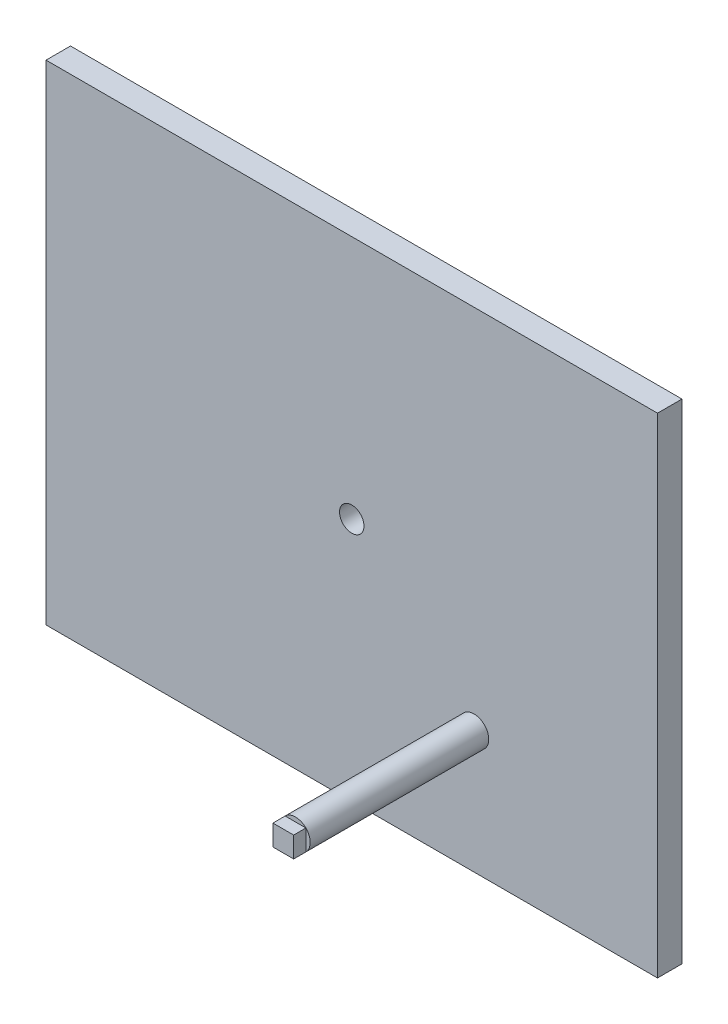
SolidWorks part; units mm, degrees
ref_plane "前视基准面" through (0, 0, 0) normal (0, 0, 1) x (1, 0, 0)
ref_plane "上视基准面" through (0, 0, 0) normal (0, 1, 0) x (1, 0, 0)
ref_plane "右视基准面" through (0, 0, 0) normal (1, 0, 0) x (0, 0, -1)
sketch "草图1" plane through (0, 0, 0) normal (0, 0, 1) x (1, 0, 0)
  line L1 (1250, -1000) -> (-1250, -1000)
  line L2 (1250, -1000) -> (1250, 1000)
  line L3 (1250, 1000) -> (-1250, 1000)
  line L4 (-1250, -1000) -> (-1250, 1000)
  line L5 (1250, -1000) -> (-1250, 1000) construction
  line L6 (1250, 1000) -> (-1250, -1000) construction
  circle A0 centre (0, 0) radius 50
  point P0 (0, 0)
  dimension "D1" = 100
  dimension "D2" = 2500
  dimension "D3" = 2000
extrude "凸台-拉伸1" add sketch "草图1" along normal blind 100
sketch "草图2" plane through (0, 0, 100) normal (0, 0, 1) x (1, 0, 0)
  circle A0 centre (500, -500) radius 60
  circle A1 centre (0, 0) radius 50 construction
  dimension "D1" = 120
  dimension "D2" = 500
  dimension "D3" = 500
extrude "凸台-拉伸2" add sketch "草图2" along normal blind 730
sketch "草图3" plane through (0, 0, 830) normal (0, 0, 1) x (1, 0, 0)
  line L1 (542.4264, -542.4264) -> (457.5736, -542.4264)
  line L2 (542.4264, -542.4264) -> (542.4264, -457.5736)
  line L3 (542.4264, -457.5736) -> (457.5736, -457.5736)
  line L4 (457.5736, -542.4264) -> (457.5736, -457.5736)
  line L5 (542.4264, -542.4264) -> (457.5736, -457.5736) construction
  line L6 (542.4264, -457.5736) -> (457.5736, -542.4264) construction
  circle A0 centre (500, -500) radius 60 construction
  point P0 (500, -500)
extrude "凸台-拉伸3" add sketch "草图3" along normal blind 50
